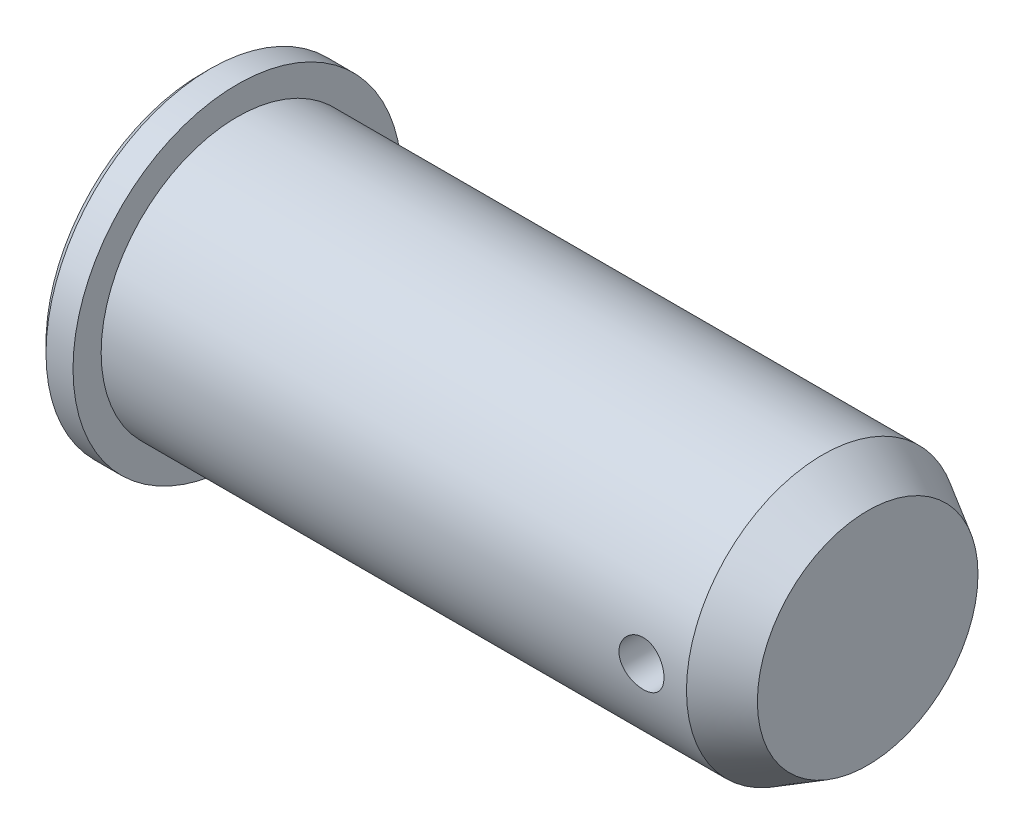
SolidWorks part; units mm, degrees
ref_plane "前视" through (0, 0, 0) normal (0, 0, 1) x (1, 0, 0)
ref_plane "上视" through (0, 0, 0) normal (0, 1, 0) x (1, 0, 0)
ref_plane "右视" through (0, 0, 0) normal (1, 0, 0) x (0, 0, -1)
sketch "草图1" plane through (0, 0, 0) normal (0, 0, 1) x (1, 0, 0)
  line L0 (0, 0) -> (0, 36.5)
  line L1 (0, 36.5) -> (8, 36.5)
  line L2 (8, 36.5) -> (8, 30.25)
  line L3 (8, 30.25) -> (138, 30.25)
  line L4 (0, 0) -> (148, 0)
  line L5 (138, 30.25) -> (148, 24.5)
  line L6 (148, 24.5) -> (148, 0)
  dimension "D1" = 36.5
  dimension "D2" = 8
  dimension "D3" = 30.25
  dimension "D4" = 130
  dimension "D5" = 24.5
  dimension "D6" = 10
revolve "旋转1" add sketch "草图1" angle 360 about L4
chamfer "倒角1" distance 2 angle 45 1 edges at (0, 0, 36.5)
ref_plane "基准面1" through (0, 0, 40) normal (0, 0, 1) x (1, 0, 0)
sketch "草图2" plane through (0, 0, 40) normal (0, 0, 1) x (1, 0, 0)
  line L0 (-1000, 0) -> (49000, 0) construction
  line L1 (128, -1000) -> (128, 49000) construction
  line L2 (8, -30.25) -> (8, 30.25) construction
  circle A0 centre (128, 0) radius 5
  dimension "D2" = 10
  dimension "D1" = 120
extrude "切除-拉伸1" cut sketch "草图2" against normal through all
